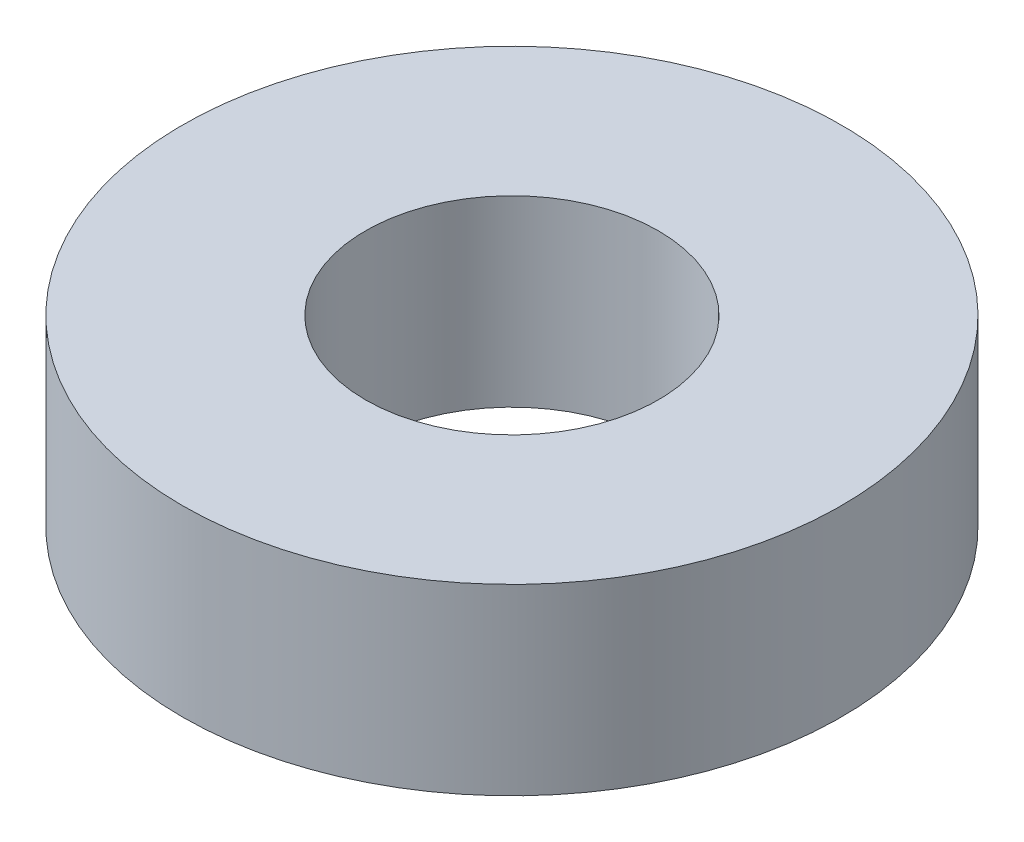
SolidWorks part; units mm, degrees
ref_plane "Front Plane" through (0, 0, 0) normal (0, 0, 1) x (1, 0, 0)
ref_plane "Top Plane" through (0, 0, 0) normal (0, 1, 0) x (1, 0, 0)
ref_plane "Right Plane" through (0, 0, 0) normal (1, 0, 0) x (0, 0, -1)
sketch "Sketch2" plane through (0, 0, 0) normal (0, 1, 0) x (1, 0, 0)
  circle A0 centre (0, 0) radius 2
  circle A1 centre (0, 0) radius 4.5
  dimension "D1" = 9
  dimension "D2" = 4
extrude "Boss-Extrude1" add sketch "Sketch2" along normal blind 2.5
